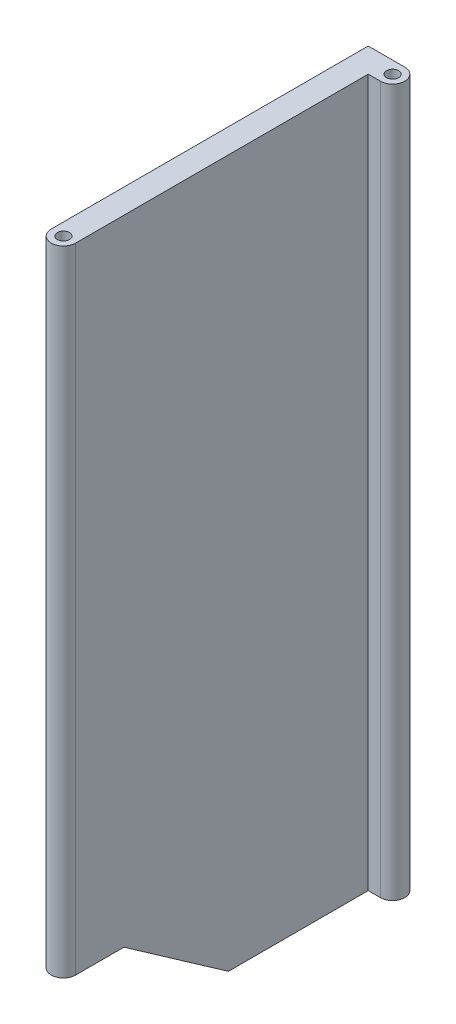
SolidWorks part; units mm, degrees
ref_plane "Спереди" through (0, 0, 0) normal (0, 0, 1) x (1, 0, 0)
ref_plane "Сверху" through (0, 0, 0) normal (0, 1, 0) x (1, 0, 0)
ref_plane "Справа" through (0, 0, 0) normal (1, 0, 0) x (0, 0, -1)
sketch "Эскиз1" plane through (0, 0, 0) normal (1, 0, 0) x (0, 0, -1)
  line L0 (-25, 6) -> (-22.035, 6)
  line L1 (-13.4661, 0) -> (0, 0)
  line L2 (0, 0) -> (0, 58)
  line L3 (0, 58) -> (-25, 58)
  line L4 (-25, 58) -> (-25, 6)
  line L5 (50, 0) -> (-50, 0) construction
  line L6 (0, 50) -> (0, -50) construction
  line L8 (-13.4661, 0) -> (-22.035, 6)
  point P5 (-12.5, 58)
  point P6 (-6.733, 0)
  dimension "D1" = 52
  dimension "D2" = 90
  dimension "D3" = 25
  dimension "D4" = 58
  dimension "D5" = 90
  dimension "D6" = 145
extrude "Бобышка-Вытянуть1" add sketch "Эскиз1" along normal blind 2
sketch "Эскиз2" plane through (0, 0, 0) normal (0, 1, 0) x (1, 0, 0)
  line L0 (-50, 0) -> (50, 0) construction
  line L1 (0, 1) -> (0, 0)
  line L2 (0, 0) -> (2, 0)
  line L3 (2, 0) -> (2, 1)
  circle A0 centre (1, 1) radius 0.5
  arc A1 (0, 1) -> (2, 1) centre (1, 1) cw
  dimension "D1" = 1
  dimension "D2" = 1
extrude "Бобышка-Вытянуть2" [suppressed] add sketch "Эскиз2" along normal blind 58
sketch "Эскиз3" plane through (0, 6, 0) normal (0, -1, 0) x (1, 0, 0)
  line L0 (2, 25) -> (0, 25) construction
  line L1 (0, 25) -> (0, 26)
  line L2 (0, 25) -> (2, 25)
  line L3 (2, 25) -> (2, 22.035) construction
  line L4 (2, 25) -> (2, 26)
  circle A0 centre (1, 26) radius 0.5
  arc A1 (0, 26) -> (2, 26) centre (1, 26) cw
  dimension "D1" = 1
  dimension "D2" = 1
extrude "Бобышка-Вытянуть3" add sketch "Эскиз3" against normal blind 52
sketch "Эскиз4" plane through (0, 0, 0) normal (0, 1, 0) x (1, 0, 0)
  line L0 (2, -13.4661) -> (2, 0) construction
  line L1 (3, 0) -> (2, 0)
  line L2 (2, 0) -> (2, -2)
  line L3 (2, -2) -> (3, -2)
  circle A0 centre (3, -1) radius 0.5
  arc A1 (3, -2) -> (3, 0) centre (3, -1) ccw
  dimension "D1" = 1
  dimension "D2" = 1
  dimension "D3" = 2
extrude "Бобышка-Вытянуть4" add sketch "Эскиз4" along normal up to surface (58 mm away) up to face at (1, 58, 13.25)
